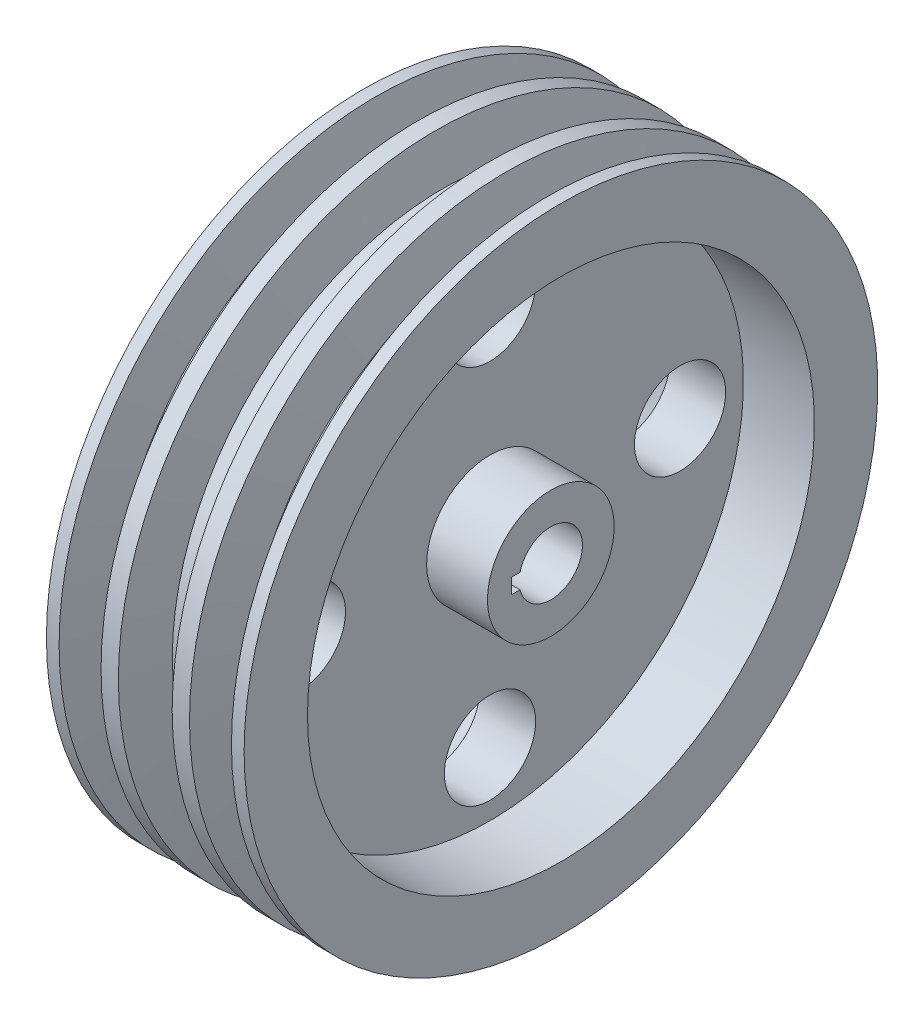
SolidWorks part; units mm, degrees
ref_plane "Front Plane" through (0, 0, 0) normal (0, 0, 1) x (1, 0, 0)
ref_plane "Top Plane" through (0, 0, 0) normal (0, 1, 0) x (1, 0, 0)
ref_plane "Right Plane" through (0, 0, 0) normal (1, 0, 0) x (0, 0, -1)
sketch "Sketch1" plane through (0, 0, 0) normal (0, 0, 1) x (1, 0, 0)
  line L0 (0, 0) -> (0, 125) construction
  line L1 (-10.6114, 125) -> (-17.4485, 125)
  line L3 (0, 12.5) -> (-35, 12.5)
  line L4 (0, 12.5) -> (35, 12.5)
  line L5 (-39, 125) -> (-39, 100)
  line L6 (-39, 100) -> (-11, 100)
  line L7 (-11, 100) -> (-11, 25)
  line L8 (-11, 25) -> (-35, 25)
  line L9 (-35, 25) -> (-35, 12.5)
  line L10 (11, 100) -> (11, 25)
  line L11 (11, 25) -> (35, 25)
  line L12 (39, 100) -> (11, 100)
  line L13 (39, 125) -> (39, 100)
  line L14 (35, 25) -> (35, 12.5)
  line L15 (-121.5853, 0) -> (165.0029, 0) construction
  line L16 (-7.3356, 107) -> (7.3356, 107)
  line L17 (-7.3356, 107) -> (-10.6114, 125)
  line L18 (-10.6114, 125) -> (-17.4485, 125)
  line L20 (-20.7243, 107) -> (-30.7243, 107)
  line L21 (-30.7243, 107) -> (-34, 125)
  line L22 (-34, 125) -> (-39, 125)
  line L23 (10.6114, 125) -> (17.4485, 125)
  line L25 (34, 125) -> (39, 125)
  line L26 (10.6114, 125) -> (17.4485, 125)
  line L27 (20.7243, 107) -> (30.7243, 107)
  line L28 (7.3356, 107) -> (10.6114, 125)
  line L29 (30.7243, 107) -> (34, 125)
  line L30 (-17.4485, 125) -> (-20.7243, 107)
  line L31 (-25.7243, 107) -> (-25.7243, 114.8779) construction
  line L32 (17.4485, 125) -> (20.7243, 107)
  point P26 (0, 107)
  point P29 (25.7243, 107)
  point P34 (0, 107)
  dimension "D2" = 125
  dimension "D3" = 12.5
  dimension "D4" = 70
  dimension "D5" = 25
  dimension "D6" = 78
  dimension "D7" = 22
  dimension "D8" = 5
  dimension "D9" = 18
  dimension "D10" = 5
  dimension "D11" = 10.6114
  dimension "D12" = 16.5515
  dimension "D13" = 25
revolve "Revolve2" add sketch "Sketch1" angle 360 about L15
sketch "Sketch2" plane through (-11, 0, 0) normal (-1, 0, 0) x (0, 0, 1)
  line L0 (0, 0) -> (0, 98.6003) construction
  line L1 (0, 0) -> (0, -95.1648) construction
  line L4 (15.5, -3) -> (15.5, 3)
  line L5 (15.5, 3) -> (12.1347, 3)
  line L6 (15.5, -3) -> (12.1347, -3)
  line L7 (15.5, 0) -> (95.6801, 0) construction
  arc A0 (12.1347, 3) -> (12.1347, -3) centre (0, 0) ccw
  circle A1 centre (0, 75) radius 18
  circle A2 centre (75, 0) radius 18
  circle A3 centre (0, -75) radius 18
  circle A4 centre (-75, 0) radius 18
  circle A5 centre (0, 0) radius 25 construction
  point P21 (0, 0)
  dimension "D1" = 75
  dimension "D3" = 36
  dimension "D4" = 12.1347
  dimension "D5" = 15.5
  dimension "D7" = 12.5
  dimension "D2" = 4
extrude "Cut-Extrude1" cut sketch "Sketch2" against normal through all both and the other way through all
